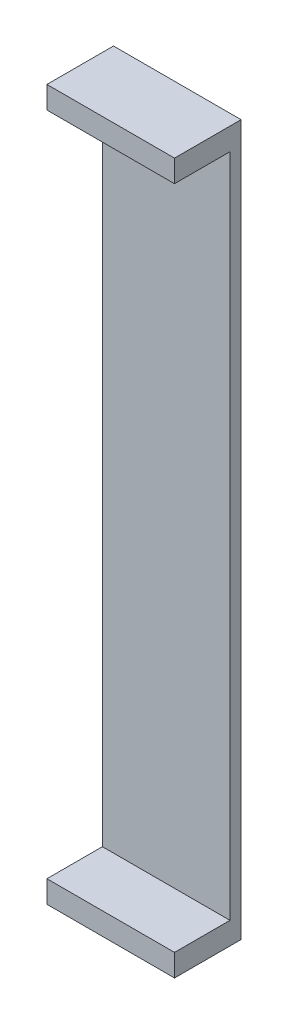
SolidWorks part; units mm, degrees
ref_plane "Front Plane" through (0, 0, 0) normal (0, 0, 1) x (1, 0, 0)
ref_plane "Top Plane" through (0, 0, 0) normal (0, 1, 0) x (1, 0, 0)
ref_plane "Right Plane" through (0, 0, 0) normal (1, 0, 0) x (0, 0, -1)
sketch "Sketch1" plane through (0, 7.0223, 0) normal (0, 0, 1) x (1, 0, 0)
  line L1 (0.6259, -6.2611) -> (23.6259, -6.2611)
  line L2 (0.6259, -6.2611) -> (0.6259, 121.7389)
  line L3 (0.6259, 121.7389) -> (23.6259, 121.7389)
  line L4 (23.6259, -6.2611) -> (23.6259, 121.7389)
  point P4 (12.1259, 121.7389)
  dimension "D1" = 128
  dimension "D2" = 23
extrude "Boss-Extrude1" add sketch "Sketch1" along normal blind 2
sketch "Sketch2" plane through (0, 7.0223, 2) normal (0, 0, 1) x (1, 0, 0)
  line L0 (0.6259, -6.2611) -> (23.6259, -6.2611) construction
  line L1 (23.6259, 121.7389) -> (0.6259, 121.7389) construction
  line L2 (23.6259, 121.7389) -> (0.6259, 121.7389)
  line L3 (23.6259, 121.7389) -> (23.6259, 117.7389)
  line L4 (23.6259, 117.7389) -> (0.6259, 117.7389)
  line L5 (23.6259, -2.2611) -> (0.6259, -2.2611)
  line L6 (23.6259, -2.2611) -> (23.6259, -6.2611)
  line L7 (23.6259, -6.2611) -> (0.6259, -6.2611)
  line L8 (0.6259, -2.2611) -> (0.6259, -6.2611)
  line L9 (23.6259, -6.2611) -> (23.6259, 121.7389) construction
  line L10 (0.6259, 121.7389) -> (0.6259, -6.2611) construction
  line L11 (0.6259, 121.7389) -> (0.6259, 117.7389)
  point P14 (0.6259, 119.7389)
  dimension "D1" = 0
  dimension "D2" = 0
  dimension "D3" = 0
  dimension "D4" = 4
  dimension "D5" = 0
  dimension "D6" = 0
  dimension "D7" = 0
  dimension "D8" = 4
extrude "Boss-Extrude2" add sketch "Sketch2" along normal blind 10
